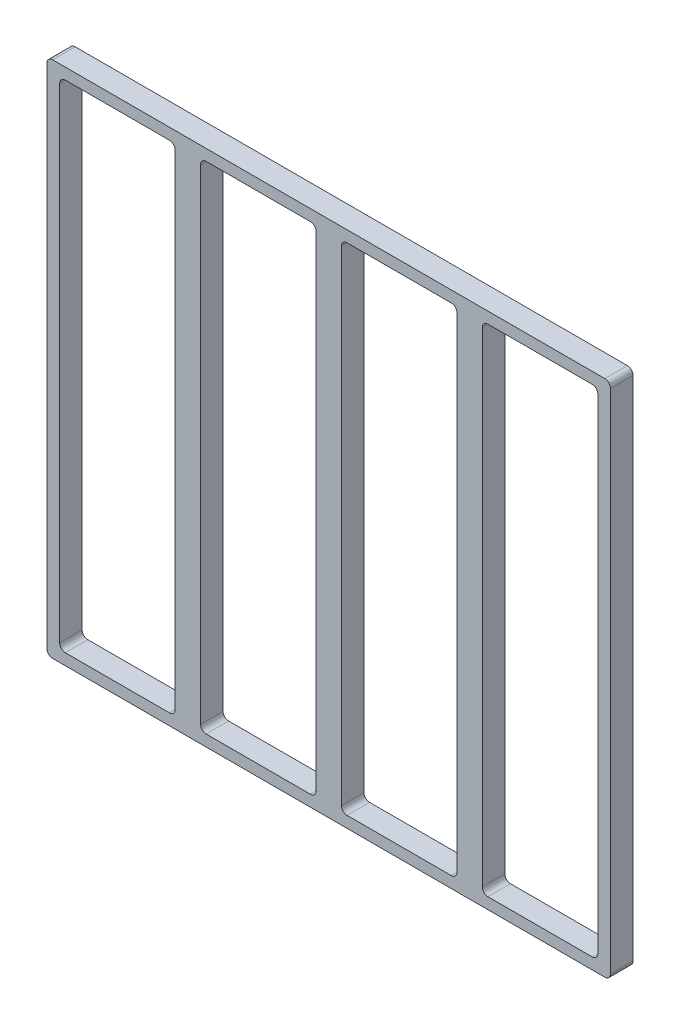
SolidWorks part; units mm, degrees
ref_plane "Front Plane" through (0, 0, 0) normal (0, 0, 1) x (1, 0, 0)
ref_plane "Top Plane" through (0, 0, 0) normal (0, 1, 0) x (1, 0, 0)
ref_plane "Right Plane" through (0, 0, 0) normal (1, 0, 0) x (0, 0, -1)
sketch "Sketch1" plane through (0, 0, 0) normal (0, 0, 1) x (1, 0, 0)
  line L0 (-47.75, 44) -> (-47.75, 0) construction
  line L1 (-49, -46) -> (49, -46)
  line L2 (-50, -45) -> (-50, 45)
  line L3 (-49, 46) -> (49, 46)
  line L4 (50, -45) -> (50, 45)
  line L5 (-50, -46) -> (50, 46) construction
  line L6 (-50, 46) -> (50, -46) construction
  line L7 (-46.75, 44) -> (-28.25, 44)
  line L8 (-47.75, 43) -> (-47.75, -43)
  line L9 (-46.75, -44) -> (-28.25, -44)
  line L10 (-27.25, 43) -> (-27.25, -43)
  line L11 (-47.75, 0) -> (-50, 0) construction
  line L12 (-22.75, 0) -> (-25, 0) construction
  line L13 (-22.75, 43) -> (-22.75, -43)
  line L14 (-21.75, 44) -> (-3.25, 44)
  line L15 (-2.25, 43) -> (-2.25, -43)
  line L16 (-21.75, -44) -> (-3.25, -44)
  line L17 (2.25, 0) -> (0, 0) construction
  line L18 (2.25, 43) -> (2.25, -43)
  line L19 (3.25, 44) -> (21.75, 44)
  line L20 (22.75, 43) -> (22.75, -43)
  line L21 (3.25, -44) -> (21.75, -44)
  line L22 (27.25, 0) -> (25, 0) construction
  line L23 (27.25, 43) -> (27.25, -43)
  line L24 (28.25, 44) -> (46.75, 44)
  line L25 (47.75, 43) -> (47.75, -43)
  line L26 (28.25, -44) -> (46.75, -44)
  arc A0 (-50, 45) -> (-49, 46) centre (-49, 45) cw
  arc A1 (49, 46) -> (50, 45) centre (49, 45) cw
  arc A2 (-49, -46) -> (-50, -45) centre (-49, -45) cw
  arc A3 (49, -46) -> (50, -45) centre (49, -45) ccw
  arc A4 (46.75, 44) -> (47.75, 43) centre (46.75, 43) cw
  arc A5 (27.25, 43) -> (28.25, 44) centre (28.25, 43) cw
  arc A6 (47.75, -43) -> (46.75, -44) centre (46.75, -43) cw
  arc A7 (27.25, -43) -> (28.25, -44) centre (28.25, -43) ccw
  arc A8 (22.75, -43) -> (21.75, -44) centre (21.75, -43) cw
  arc A9 (2.25, -43) -> (3.25, -44) centre (3.25, -43) ccw
  arc A10 (21.75, 44) -> (22.75, 43) centre (21.75, 43) cw
  arc A11 (2.25, 43) -> (3.25, 44) centre (3.25, 43) cw
  arc A12 (-3.25, 44) -> (-2.25, 43) centre (-3.25, 43) cw
  arc A13 (-22.75, 43) -> (-21.75, 44) centre (-21.75, 43) cw
  arc A14 (-2.25, -43) -> (-3.25, -44) centre (-3.25, -43) cw
  arc A15 (-22.75, -43) -> (-21.75, -44) centre (-21.75, -43) ccw
  arc A16 (-28.25, -44) -> (-27.25, -43) centre (-28.25, -43) ccw
  arc A17 (-47.75, -43) -> (-46.75, -44) centre (-46.75, -43) ccw
  arc A18 (-28.25, 44) -> (-27.25, 43) centre (-28.25, 43) cw
  arc A19 (-46.75, 44) -> (-47.75, 43) centre (-46.75, 43) ccw
  point P0 (0, 0)
  point P70 (-47.75, -44)
  point P73 (-27.25, 44)
  dimension "D8" = 1
  dimension "D1" = 100
  dimension "D2" = 92
  dimension "D3" = 20.5
  dimension "D4" = 88
  dimension "D6" = 2.25
  dimension "D7" = 2.25
  dimension "D5" = 4
extrude "Boss-Extrude1" add sketch "Sketch1" along normal blind 4
